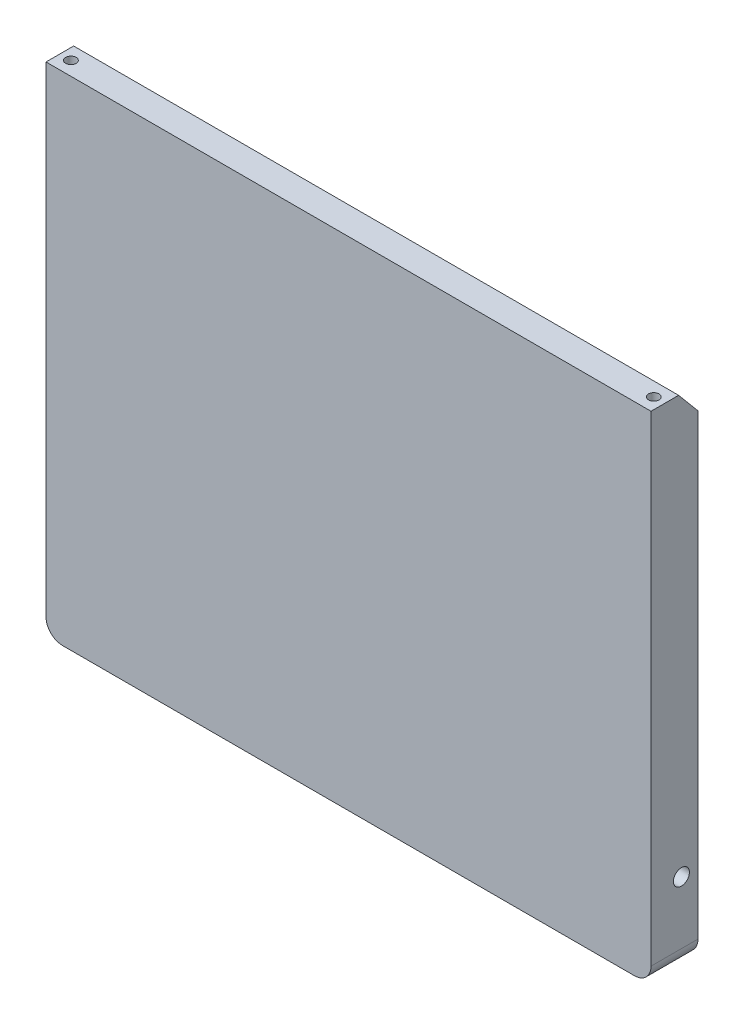
SolidWorks part; units mm, degrees
ref_plane "Front Plane" through (0, 0, 0) normal (0, 0, 1) x (1, 0, 0)
ref_plane "Top Plane" through (0, 0, 0) normal (0, 1, 0) x (1, 0, 0)
ref_plane "Right Plane" through (0, 0, 0) normal (1, 0, 0) x (0, 0, -1)
sketch "Sketch1" plane through (0, 0, 0) normal (0, 0, 1) x (1, 0, 0)
  line L1 (-5.3066, -80.8019) -> (104.2134, -80.8019)
  line L2 (-5.3066, -80.8019) -> (-5.3066, 9.1981)
  line L3 (-5.3066, 9.1981) -> (104.2134, 9.1981)
  line L4 (104.2134, -80.8019) -> (104.2134, 9.1981)
  dimension "D1" = 109.52
  dimension "D2" = 90
extrude "Boss-Extrude1" add sketch "Sketch1" along normal blind 5
sketch "Sketch2" plane through (0, 9.1981, 0) normal (0, 1, 0) x (1, 0, 0)
  line L0 (-5.3066, -5) -> (-5.3066, 0) construction
  line L1 (104.2134, -5) -> (104.2134, 0) construction
  circle A0 centre (-3.3066, -2.5) radius 0.95
  circle A1 centre (102.2134, -2.5) radius 0.95
  point P4 (0, 0)
  point P7 (-5.3066, -2.5)
  point P8 (0, 0)
  dimension "D2" = 1.9
  dimension "D4" = 1.9
  dimension "D1" = 2
  dimension "D3" = 2
extrude "Cut-Extrude1" cut sketch "Sketch2" against normal blind 7 contours A1 | A0
fillet "Fillet1" radius 3 2 edges at (104.2134, -80.8019, 2.5) (-5.3066, -80.8019, 2.5)
sketch "Sketch4" plane through (0, 0, 0) normal (0, 0, -1) x (-1, 0, 0)
  line L4 (-104.2134, 9.1981) -> (-104.2134, -77.8019)
  line L5 (-101.2134, -80.8019) -> (2.3066, -80.8019)
  line L6 (5.3066, -77.8019) -> (5.3066, 9.1981)
  line L7 (5.3066, 9.1981) -> (-104.2134, 9.1981)
  line L8 (-104.2134, 9.1981) -> (-104.2134, -77.8019)
  line L9 (-101.2134, -80.8019) -> (2.3066, -80.8019)
  line L10 (5.3066, -77.8019) -> (5.3066, 9.1981)
  line L11 (5.3066, 9.1981) -> (-104.2134, 9.1981)
  arc A2 (-104.2134, -77.8019) -> (-101.2134, -80.8019) centre (-101.2134, -77.8019) ccw
  arc A3 (2.3066, -80.8019) -> (5.3066, -77.8019) centre (2.3066, -77.8019) ccw
  arc A4 (-104.2134, -77.8019) -> (-101.2134, -80.8019) centre (-101.2134, -77.8019) ccw
  arc A5 (2.3066, -80.8019) -> (5.3066, -77.8019) centre (2.3066, -77.8019) ccw
  dimension "D1" = 0
extrude "Boss-Extrude2" add sketch "Sketch4" along normal blind 3.5
sketch "Sketch5" plane through (0, 0, -3.5) normal (0, 0, -1) x (-1, 0, 0)
  line L0 (-49.4534, 9.1981) -> (-49.4534, -80.8019) construction
  line L1 (-99.5534, 3.7981) -> (0.6466, 3.7981)
  line L2 (-99.5534, 3.7981) -> (-99.5534, -75.4019)
  line L3 (-99.5534, -75.4019) -> (0.6466, -75.4019)
  line L4 (0.6466, 3.7981) -> (0.6466, -75.4019)
  line L5 (5.3066, 9.1981) -> (-104.2134, 9.1981) construction
  line L6 (-101.2134, -80.8019) -> (2.3066, -80.8019) construction
  point P10 (-49.4534, 3.7981)
  point P11 (-99.5534, -35.8019)
  point P12 (-49.4534, -35.8019)
  dimension "D1" = 100.2
  dimension "D2" = 79.2
chamfer "Chamfer1" distance 3.5 angle 50 1 edges at (49.4534, 9.1981, -3.5)
ref_plane "Plane1" through (49.4534, 0, 0) normal (-1, 0, 0) x (0, 0, 1)
extrude "Cut-Extrude3" cut sketch "Sketch5" against normal blind 6.5
sketch "Sketch8" plane through (104.2134, 0, 0) normal (1, 0, 0) x (0, 0, -1)
  line L2 (0.5, -68.0019) -> (0.5, -65.1019) construction
  circle A2 centre (0.5, -66.5519) radius 1.45
extrude "Cut-Extrude5" cut sketch "Sketch8" against normal blind 3
mirror "Mirror2" about plane through (49.4534, 0, 0) normal (-1, 0, 0) of "Cut-Extrude5"
